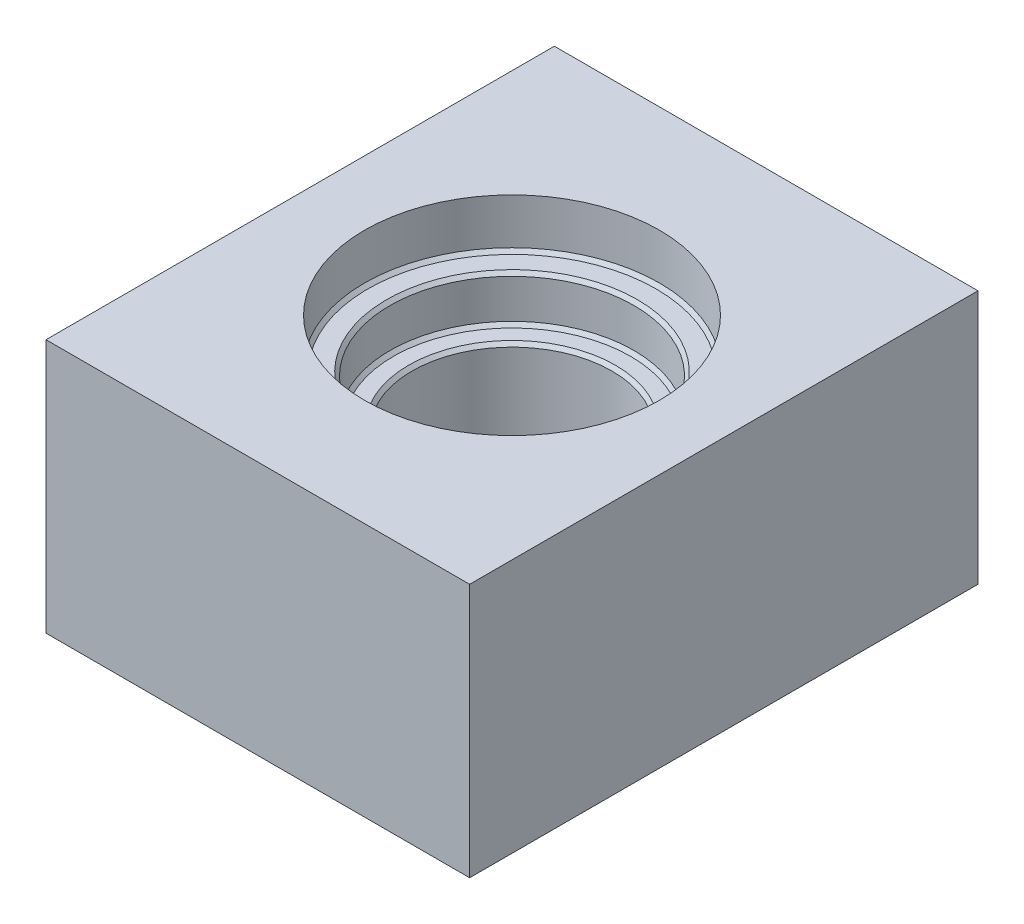
SolidWorks part; units mm, degrees
material "Gray Cast Iron"
ref_plane "Front Plane" through (0, 0, 0) normal (0, 0, 1) x (1, 0, 0)
ref_plane "Top Plane" through (0, 0, 0) normal (0, 1, 0) x (1, 0, 0)
ref_plane "Right Plane" through (0, 0, 0) normal (1, 0, 0) x (0, 0, -1)
sketch "Sketch1" plane through (0, 0, 0) normal (0, 0, 1) x (1, 0, 0)
  line L1 (-125, 0) -> (125, 0)
  line L2 (-125, 0) -> (-125, 150)
  line L3 (-125, 150) -> (125, 150)
  line L4 (125, 0) -> (125, 150)
  point P4 (0, 0)
  dimension "D1" = 150
  dimension "D2" = 250
extrude "Boss-Extrude1" add sketch "Sketch1" against normal blind 150
sketch "Sketch2" plane through (0, 0, 0) normal (0, 0, 1) x (1, 0, 0)
  line L0 (0, 0) -> (0, 101.8695) construction
  line L1 (0, 150) -> (87, 150)
  line L2 (125, 150) -> (-125, 150) construction
  line L3 (87, 150) -> (87, 123)
  line L4 (85, 121) -> (74, 121)
  line L5 (72, 119) -> (72, 96)
  line L6 (70, 94) -> (61, 94)
  line L7 (59, 92) -> (59, 46)
  line L8 (57, 44) -> (43, 44)
  line L9 (41, 42) -> (41, 36)
  line L10 (39, 34) -> (0, 34)
  line L11 (0, 34) -> (0, 150)
  line L12 (87, 123) -> (85, 121)
  line L13 (74, 121) -> (72, 119)
  line L14 (72, 96) -> (70, 94)
  line L15 (61, 94) -> (59, 92)
  line L16 (59, 46) -> (57, 44)
  line L17 (43, 44) -> (41, 42)
  line L18 (41, 36) -> (39, 34)
  point P7 (87, 121)
  point P8 (72, 121)
  point P10 (72, 94)
  point P11 (59, 94)
  point P12 (59, 44)
  point P13 (41, 44)
  point P14 (41, 34)
  dimension "D1" = 87
  dimension "D2" = 72
  dimension "D3" = 59
  dimension "D4" = 29
  dimension "D5" = 27
  dimension "D6" = 10
  dimension "D7" = 50
  dimension "D8" = 41
  dimension "D9" = 2
  dimension "D10" = 45
  dimension "D11" = 2
  dimension "D12" = 45
  dimension "D13" = 2
  dimension "D14" = 45
  dimension "D15" = 2
  dimension "D16" = 45
  dimension "D17" = 2
  dimension "D18" = 45
  dimension "D19" = 2
  dimension "D20" = 45
  dimension "D21" = 2
  dimension "D22" = 45
revolve "Cut-Revolve1" cut sketch "Sketch2" angle 360 about L0
mirror "Mirror1" about plane through (0, 0, 0) normal (0, 0, -1) of "Cut-Revolve1", "Boss-Extrude1"
